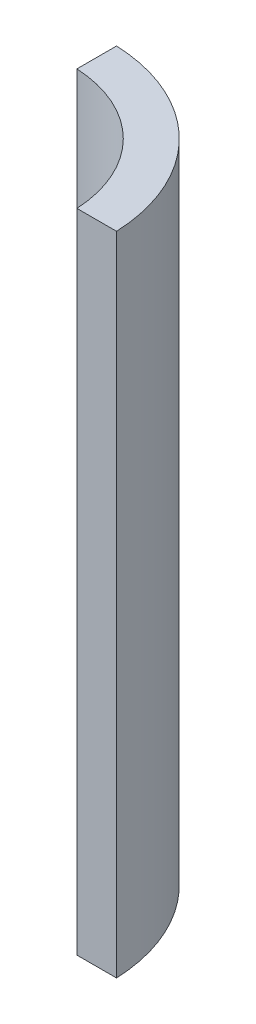
SolidWorks part; units mm, degrees
ref_plane "Front Plane" through (0, 0, 0) normal (0, 0, 1) x (1, 0, 0)
ref_plane "Top Plane" through (0, 0, 0) normal (0, 1, 0) x (1, 0, 0)
ref_plane "Right Plane" through (0, 0, 0) normal (1, 0, 0) x (0, 0, -1)
sketch "Sketch1" plane through (0, 0, 0) normal (0, 1, 0) x (1, 0, 0)
  line L1 (1.5, -37.9704) -> (-1.5, -37.9704)
  line L2 (1.5, -37.9704) -> (1.5, 37.9704)
  line L3 (1.5, 37.9704) -> (-1.5, 37.9704)
  line L4 (-1.5, -37.9704) -> (-1.5, 37.9704)
  line L5 (1.5, -37.9704) -> (-1.5, 37.9704) construction
  line L6 (1.5, 37.9704) -> (-1.5, -37.9704) construction
  line L7 (-37.9704, -1.5) -> (37.9704, -1.5)
  line L8 (-37.9704, -1.5) -> (-37.9704, 1.5)
  line L9 (-37.9704, 1.5) -> (37.9704, 1.5)
  line L10 (37.9704, -1.5) -> (37.9704, 1.5)
  line L11 (-37.9704, -1.5) -> (37.9704, 1.5) construction
  line L12 (-37.9704, 1.5) -> (37.9704, -1.5) construction
  circle A0 centre (0, 0) radius 38
  circle A1 centre (0, 0) radius 29
  dimension "D1" = 58
  dimension "D2" = 76
  dimension "D3" = 3
  dimension "D4" = 3
extrude "Boss-Extrude1" add sketch "Sketch1" along normal blind 147 contours A1 L9 A0 L2
